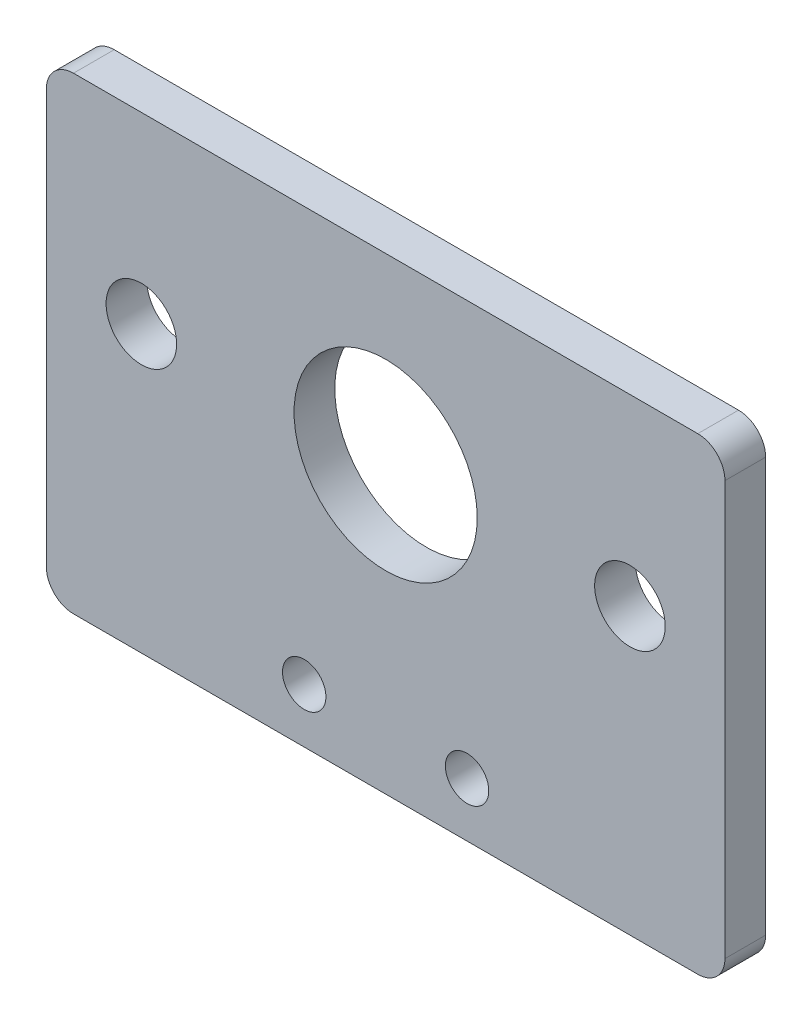
SolidWorks part; units mm, degrees
material "环氧树脂,未充填"
ref_plane "Front" through (0, 0, 0) normal (0, 0, 1) x (1, 0, 0)
ref_plane "Top" through (0, 0, 0) normal (0, 1, 0) x (1, 0, 0)
ref_plane "Right" through (0, 0, 0) normal (1, 0, 0) x (0, 0, -1)
sketch "草图1" plane through (0, 0, 0) normal (0, 0, 1) x (1, 0, 0)
  line L0 (25, 0) -> (25, -42) construction
  line L1 (2, 0) -> (48, 0)
  line L2 (0, -2) -> (0, -40)
  line L3 (2, -42) -> (48, -42)
  line L4 (50, -2) -> (50, -40)
  line L5 (15, -21) -> (50015, -21) construction
  arc A0 (48, 0) -> (50, -2) centre (48, -2) cw
  arc A1 (0, -40) -> (2, -42) centre (2, -40) ccw
  arc A2 (48, -42) -> (50, -40) centre (48, -40) ccw
  arc A3 (2, 0) -> (0, -2) centre (2, -2) ccw
  circle A4 centre (25, -21) radius 6.75
  circle A9 centre (43, -21) radius 2.6
  circle A11 centre (7, -21) radius 2.6
  point P7 (50, 0)
  point P10 (0, -42)
  point P15 (0, 0)
  point P29 (25, -21)
  dimension "D3" = 2
  dimension "D4" = 13.5
  dimension "D5" = 5.2
  dimension "D6" = 36
  dimension "D1" = 42
  dimension "D2" = 50
extrude "凸台-拉伸1" add sketch "草图1" along normal blind 3
sketch "草图2" plane through (0, 0, 0) normal (0, 0, -1) x (-1, 0, 0)
  line L1 (-50, -21) -> (0, -21) construction
  line L2 (-50, -40) -> (-50, -2) construction
  line L3 (0, -2) -> (0, -40) construction
  line L4 (-2, -42) -> (-48, -42) construction
  line L5 (-25, -21) -> (-25, -50021) construction
  circle A2 centre (-19, -38) radius 1.6
  circle A4 centre (-31, -38) radius 1.6
  point P2 (-25, -21)
  dimension "D1" = 12
  dimension "D2" = 4
  dimension "D3" = 3.2
extrude "切除-拉伸1" cut sketch "草图2" against normal blind 10
sketch "草图3" plane through (0, 0, 3) normal (0, 0, 1) x (1, 0, 0)
  line L0 (-5.8739, -7.5) -> (53.4838, -7.5)
  line L1 (53.4838, -7.5) -> (53.4838, 10.3165)
  line L2 (53.4838, 10.3165) -> (-5.8739, 10.3165)
  line L3 (-5.8739, 10.3165) -> (-5.8739, -7.5)
  line L4 (25, -14.25) -> (25, -50014.25) construction
  line L5 (25, -21) -> (50025, -21) construction
  dimension "D1" = 13.5
extrude "切除-拉伸2" cut sketch "草图3" against normal blind 10
fillet "圆角1" radius 2 2 edges at (50, -7.5, 1.5) (0, -7.5, 1.5)
equation "\"13。5\"=13.6835"
